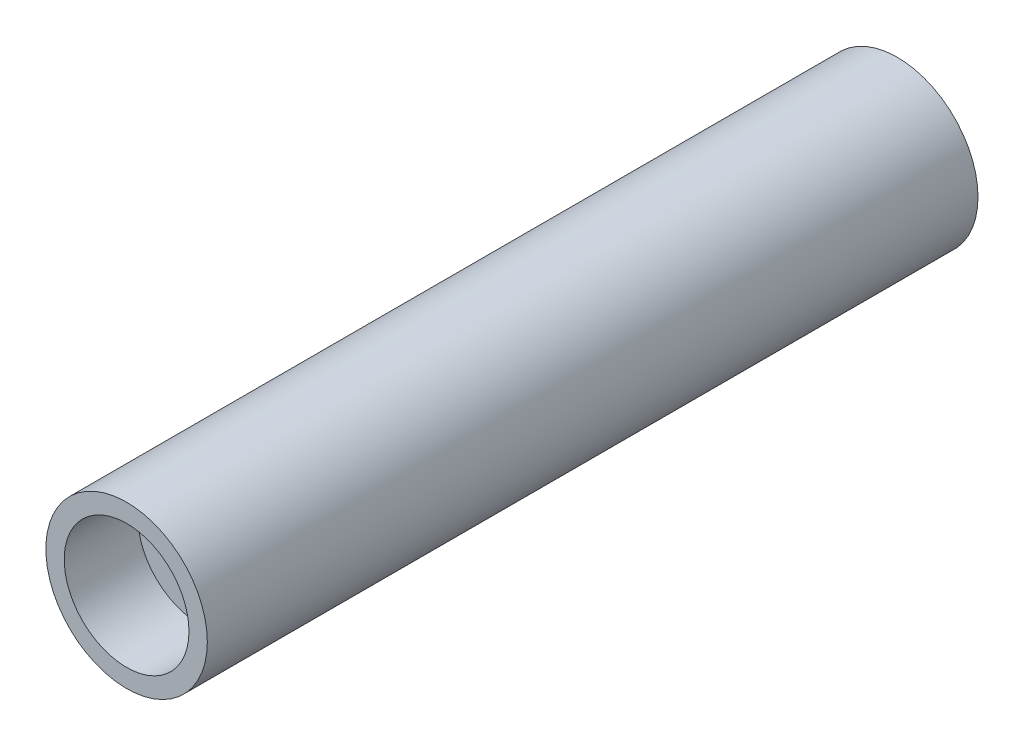
SolidWorks part; units mm, degrees
material "Pine"
ref_plane "Front Plane" through (0, 0, 0) normal (0, 0, 1) x (1, 0, 0)
ref_plane "Top Plane" through (0, 0, 0) normal (0, 1, 0) x (1, 0, 0)
ref_plane "Right Plane" through (0, 0, 0) normal (1, 0, 0) x (0, 0, -1)
sketch "Sketch2" plane through (0, 0, 0) normal (0, 0, 1) x (1, 0, 0)
  circle A0 centre (0, 0) radius 17
  circle A1 centre (0, 0) radius 22
  dimension "D1" = 34
  dimension "D2" = 44
extrude "Boss-Extrude1" add sketch "Sketch2" along normal blind 210
sketch "Sketch3" plane through (0, 0, 210) normal (0, 0, 1) x (1, 0, 0)
  circle A0 centre (0, 0) radius 16.95
  circle A1 centre (0, 0) radius 5
  point P4 (0, 0)
  dimension "D1" = 33.9
  dimension "D2" = 10
extrude "Boss-Extrude2" add sketch "Sketch3" against normal offset from surface (150 mm away) 170 from offset 20 up to face at (22, 0, 210) offset against normal yes
